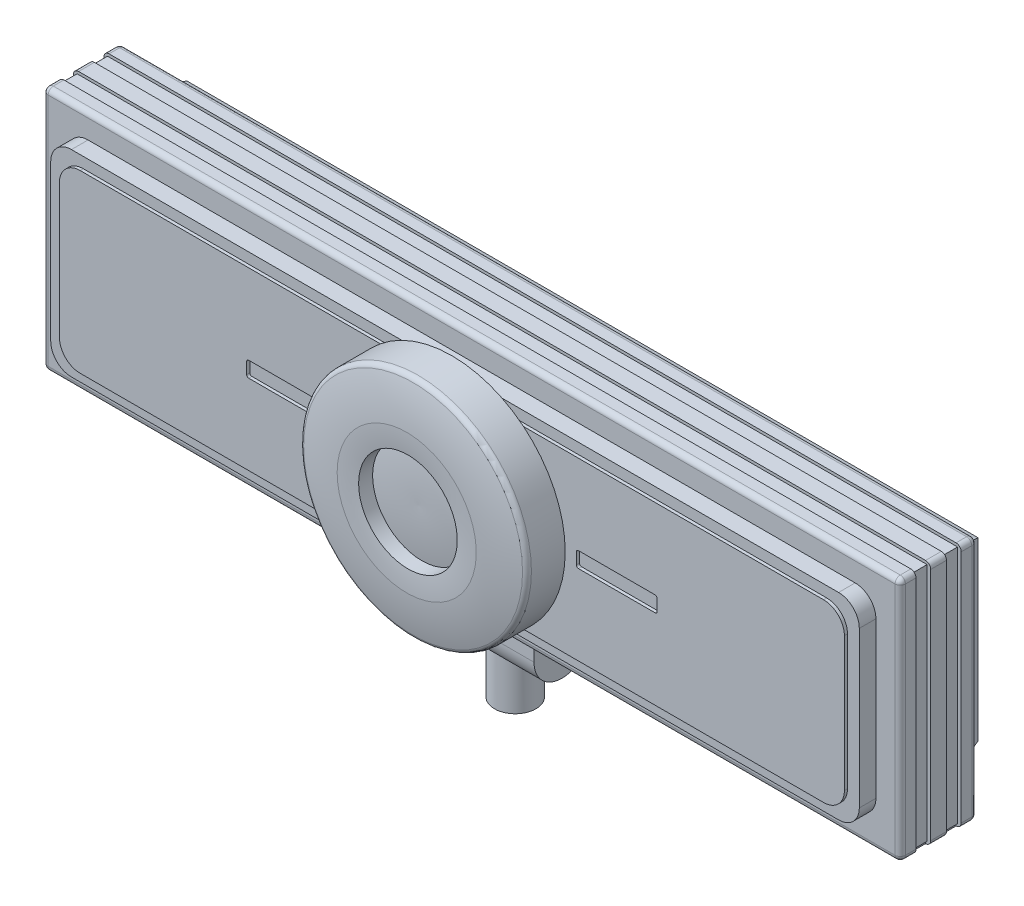
SolidWorks part; units mm, degrees
ref_plane "Front Plane" through (0, 0, 0) normal (0, 0, 1) x (1, 0, 0)
ref_plane "Top Plane" through (0, 0, 0) normal (0, 1, 0) x (1, 0, 0)
ref_plane "Right Plane" through (0, 0, 0) normal (1, 0, 0) x (0, 0, -1)
sketch "Sketch1" plane through (0, 0, 0) normal (0, 0, 1) x (1, 0, 0)
  line L1 (-52.5145, -15.0241) -> (52.5145, -15.0241)
  line L2 (-52.5145, -15.0241) -> (-52.5145, 15.0241)
  line L3 (-52.5145, 15.0241) -> (52.5145, 15.0241)
  line L4 (52.5145, -15.0241) -> (52.5145, 15.0241)
  line L5 (-52.5145, -15.0241) -> (52.5145, 15.0241) construction
  line L6 (-52.5145, 15.0241) -> (52.5145, -15.0241) construction
  point P0 (0, 0)
  dimension "D1" = 105.029
  dimension "D2" = 30.0482
extrude "Boss-Extrude1" add sketch "Sketch1" along normal blind 1.9304
sketch "Sketch2" plane through (0, 0, 1.9304) normal (0, 0, 1) x (1, 0, 0)
  line L1 (-52.07, -14.6812) -> (52.07, -14.6812)
  line L2 (-52.07, -14.6812) -> (-52.07, 14.6812)
  line L3 (-52.07, 14.6812) -> (52.07, 14.6812)
  line L4 (52.07, -14.6812) -> (52.07, 14.6812)
  line L5 (-52.07, -14.6812) -> (52.07, 14.6812) construction
  line L6 (-52.07, 14.6812) -> (52.07, -14.6812) construction
  point P0 (0, 0)
  dimension "D1" = 104.14
  dimension "D2" = 29.3624
extrude "Boss-Extrude2" add sketch "Sketch2" along normal blind 1.9304
sketch "Sketch3" plane through (0, 0, 0) normal (0, 1, 0) x (1, 0, 0)
  line L0 (0, 30.039) -> (0, -36.4807) construction
pattern_linear "LPattern1" count 2 spacing 3.7338 along (0, 0, 1) of "Boss-Extrude1", "Boss-Extrude2"
pattern_linear "LPattern2" count 2 spacing 7.4676 along (0, 0, 1) of "Boss-Extrude1"
sketch "Sketch4" plane through (0, 0, 0) normal (0, 0, -1) x (-1, 0, 0)
  line L1 (-49.4538, -11.938) -> (49.4538, -11.938)
  line L2 (-49.4538, -11.938) -> (-49.4538, 11.938)
  line L3 (-49.4538, 11.938) -> (49.4538, 11.938)
  line L4 (49.4538, -11.938) -> (49.4538, 11.938)
  line L5 (-49.4538, -11.938) -> (49.4538, 11.938) construction
  line L6 (-49.4538, 11.938) -> (49.4538, -11.938) construction
  point P0 (0, 0)
  dimension "D1" = 23.876
  dimension "D2" = 98.9076
ref_plane "Plane1" through (0, 0, -4.191) normal (0, 0, -1) x (-1, 0, 0)
sketch "Sketch5" plane through (0, 0, -4.191) normal (0, 0, -1) x (-1, 0, 0)
  line L1 (-48.4505, -10.795) -> (48.4505, -10.795)
  line L2 (-48.4505, -10.795) -> (-48.4505, 10.795)
  line L3 (-48.4505, 10.795) -> (48.4505, 10.795)
  line L4 (48.4505, -10.795) -> (48.4505, 10.795)
  line L5 (-48.4505, -10.795) -> (48.4505, 10.795) construction
  line L6 (-48.4505, 10.795) -> (48.4505, -10.795) construction
  point P0 (0, 0)
  dimension "D1" = 21.59
  dimension "D2" = 96.901
loft "Loft1" add profiles "Sketch4", "Sketch5"
fillet "Fillet1" radius 0.635 20 edges at (52.5145, 15.0241, 8.4328) (52.5145, 15.0241, 0.9652) (52.5145, 15.0241, 4.699) (52.5145, -15.0241, 8.4328) (52.5145, -15.0241, 4.699) (52.5145, -15.0241, 0.9652) (-52.5145, -15.0241, 8.4328) (-52.5145, -15.0241, 4.699) (-52.5145, -15.0241, 0.9652) (-52.5145, 15.0241, 8.4328) (-52.5145, 15.0241, 0.9652) (-52.5145, 15.0241, 4.699) (-52.5145, 0, 0) (0, -15.0241, 0) (52.5145, 0, 0) (0, 15.0241, 0) (-52.5145, 0, 9.398) (0, -15.0241, 9.398) (52.5145, 0, 9.398) (0, 15.0241, 9.398)
sketch "Sketch7" plane through (0, -14.6812, 0) normal (0, -1, 0) x (1, 0, 0)
  line L1 (-51.8795, 7.4676) -> (51.8795, 7.4676)
  line L2 (-51.8795, 7.4676) -> (-51.8795, 1.9304)
  line L3 (-51.8795, 1.9304) -> (51.8795, 1.9304)
  line L4 (51.8795, 7.4676) -> (51.8795, 1.9304)
extrude "Boss-Extrude3" add sketch "Sketch7" along normal up to surface (0.3429 mm away) up to face at (0, -15.0241, 8.1153)
sketch "Sketch8" plane through (0, 0, 9.398) normal (0, 0, 1) x (1, 0, 0)
  line L1 (-46.99, -12.065) -> (46.99, -12.065)
  line L2 (-49.53, -9.525) -> (-49.53, 9.525)
  line L3 (-46.99, 12.065) -> (46.99, 12.065)
  line L4 (49.53, -9.525) -> (49.53, 9.525)
  line L5 (-49.53, -12.065) -> (49.53, 12.065) construction
  line L6 (-49.53, 12.065) -> (49.53, -12.065) construction
  arc A0 (-49.53, 9.525) -> (-46.99, 12.065) centre (-46.99, 9.525) cw
  arc A1 (-49.53, -9.525) -> (-46.99, -12.065) centre (-46.99, -9.525) ccw
  arc A2 (46.99, -12.065) -> (49.53, -9.525) centre (46.99, -9.525) ccw
  arc A3 (49.53, 9.525) -> (46.99, 12.065) centre (46.99, 9.525) ccw
  point P0 (0, 0)
  dimension "D3" = 2.54
  dimension "D1" = 24.13
  dimension "D2" = 99.06
extrude "Boss-Extrude4" add sketch "Sketch8" along normal blind 2.032
sketch "Sketch9" plane through (0, 0, 11.43) normal (0, 0, 1) x (1, 0, 0)
  line L1 (-45.5422, -10.7569) -> (45.5422, -10.7569)
  line L2 (-48.0822, -8.2169) -> (-48.0822, 8.2169)
  line L3 (-45.5422, 10.7569) -> (45.5422, 10.7569)
  line L4 (48.0822, -8.2169) -> (48.0822, 8.2169)
  line L5 (-48.0822, -10.7569) -> (48.0822, 10.7569) construction
  line L6 (-48.0822, 10.7569) -> (48.0822, -10.7569) construction
  arc A0 (45.5422, 10.7569) -> (48.0822, 8.2169) centre (45.5422, 8.2169) cw
  arc A1 (48.0822, -8.2169) -> (45.5422, -10.7569) centre (45.5422, -8.2169) cw
  arc A2 (-48.0822, -8.2169) -> (-45.5422, -10.7569) centre (-45.5422, -8.2169) ccw
  arc A3 (-48.0822, 8.2169) -> (-45.5422, 10.7569) centre (-45.5422, 8.2169) cw
  point P0 (0, 0)
  dimension "D3" = 2.54
  dimension "D1" = 21.5138
  dimension "D2" = 96.1644
extrude "Boss-Extrude5" add sketch "Sketch9" along normal blind 0.381
sketch "Sketch11" plane through (0, 0, 0) normal (0, 1, 0) x (1, 0, 0)
  line L0 (0, -11.811) -> (0, -15.875)
  line L1 (-45.5422, -11.811) -> (45.5422, -11.811) construction
  line L2 (0, 30.039) -> (0, -36.4807) construction
  line L3 (0, -11.811) -> (13.8811, -11.811)
  line L4 (13.8811, -11.811) -> (13.8811, -16.4338)
  line L5 (0, -11.811) -> (0, -24.9316) construction
  line L6 (8.5217, -11.43) -> (8.5217, -17.3482)
  line L7 (-45.5422, -11.43) -> (45.5422, -11.43) construction
  line L8 (6.0452, -11.811) -> (6.0452, -17.1958)
  spline S0 degree 2 poles (8.5217, -17.3482) (11.2515, -17.184) (13.8811, -16.4338) knots 0 0 0 1 1 1
  spline S1 degree 2 poles (8.5217, -17.3482) (7.2787, -17.3449) (6.0452, -17.1958) knots 0 0 0 1 1 1
  spline S2 degree 2 poles (0, -15.875) (3.0436, -15.9753) (6.0452, -15.4815) knots 0 0 0 1 1 1
  dimension "D1" = 13.8811
  dimension "D2" = 4.064
  dimension "D3" = 4.6228
  dimension "D4" = 8.5217
  dimension "D5" = 5.9182
  dimension "D6" = 5.3848
  dimension "D7" = 6.0452
revolve "Revolve2" add sketch "Sketch11" angle 360 about L5
sketch "Sketch14" plane through (0, 0, 0) normal (0, 1, 0) x (1, 0, 0)
  line L0 (-8.7735, -11.811) -> (8.7735, -11.811) construction
  line L1 (0, -14.1732) -> (0, -11.811)
  line L2 (0, -11.811) -> (2.3622, -11.811)
  arc A0 (0, -14.1732) -> (2.3622, -11.811) centre (0, -11.811) ccw
  dimension "D1" = 4.7244
revolve "Revolve3" add sketch "Sketch14" angle 360 about L0
fillet "Fillet2" radius 0.635 1 edges at (-13.8811, 0, 16.4338)
sketch "Sketch15" plane through (0, 0, 11.811) normal (0, 0, 1) x (1, 0, 0)
  line L0 (-48.0822, 0) -> (48.0822, 0) construction
  line L1 (-48.0822, 8.2169) -> (-48.0822, -8.2169) construction
  line L2 (48.0822, -8.2169) -> (48.0822, 8.2169) construction
  line L3 (0, 13.4084) -> (0, -13.4084) construction
  line L4 (-15.24, 0.9525) -> (-25.146, -0.9525) construction
  line L5 (15.494, -0.9525) -> (24.892, -0.9525)
  line L6 (15.24, -0.6985) -> (15.24, 0.6985)
  line L7 (15.494, 0.9525) -> (24.892, 0.9525)
  line L8 (25.146, -0.6985) -> (25.146, 0.6985)
  line L9 (15.24, -0.9525) -> (25.146, 0.9525) construction
  line L10 (15.24, 0.9525) -> (25.146, -0.9525) construction
  line L11 (-15.24, -0.9525) -> (-25.146, 0.9525) construction
  line L12 (-25.146, -0.6985) -> (-25.146, 0.6985)
  line L13 (-15.494, 0.9525) -> (-24.892, 0.9525)
  line L14 (-15.24, -0.6985) -> (-15.24, 0.6985)
  line L15 (-15.494, -0.9525) -> (-24.892, -0.9525)
  circle A0 centre (0, 0) radius 13.4084 construction
  arc A1 (15.24, 0.6985) -> (15.494, 0.9525) centre (15.494, 0.6985) cw
  arc A2 (15.494, -0.9525) -> (15.24, -0.6985) centre (15.494, -0.6985) cw
  arc A3 (25.146, -0.6985) -> (24.892, -0.9525) centre (24.892, -0.6985) cw
  arc A4 (25.146, 0.6985) -> (24.892, 0.9525) centre (24.892, 0.6985) ccw
  arc A5 (-25.146, 0.6985) -> (-24.892, 0.9525) centre (-24.892, 0.6985) cw
  arc A6 (-25.146, -0.6985) -> (-24.892, -0.9525) centre (-24.892, -0.6985) ccw
  arc A7 (-15.494, -0.9525) -> (-15.24, -0.6985) centre (-15.494, -0.6985) ccw
  arc A8 (-15.24, 0.6985) -> (-15.494, 0.9525) centre (-15.494, 0.6985) ccw
  point P11 (20.193, 0)
  point P45 (-20.193, 0)
  dimension "D3" = 0.254
  dimension "D1" = 1.905
  dimension "D2" = 9.906
  dimension "D4" = 15.24
extrude "Cut-Extrude1" cut sketch "Sketch15" against normal blind 0.381
sketch "Sketch16" plane through (0, 0, 0) normal (1, 0, 0) x (0, 0, -1)
  line L0 (-0.635, -15.0241) -> (-7.4676, -15.0241)
  line L1 (-7.4676, -15.0241) -> (-7.4676, -17.9578)
  line L2 (-0.635, -15.0241) -> (-0.635, -17.9578)
  line L3 (-4.0513, -15.0241) -> (-4.0513, -21.3741) construction
  arc A0 (-7.4676, -17.9578) -> (-0.635, -17.9578) centre (-4.0513, -17.9578) ccw
  dimension "D1" = 6.35
extrude "Boss-Extrude6" add sketch "Sketch16" against normal mid plane 11.43
sketch "Sketch18" plane through (0, -15.0241, 0) normal (0, -1, 0) x (-1, 0, 0)
  line L0 (0, -8.4848) -> (0, -1.7932) construction
  line L1 (0, 30.039) -> (0, -36.4807) construction
  line L2 (4.3625, -4.0513) -> (0, -4.0513) construction
  line L4 (5.715, -4.0513) -> (-5.715, -4.0513) construction
  circle A0 centre (0, -4.0513) radius 2.54
  dimension "D1" = 5.08
extrude "Boss-Extrude7" add sketch "Sketch18" along normal blind 11.176
sketch "Sketch20" plane through (0, 0, 0) normal (1, 0, 0) x (0, 0, -1)
  line L0 (4.191, 0) -> (11.684, 0)
  line L1 (4.191, 10.795) -> (4.191, -10.795) construction
  line L2 (4.191, 6.604) -> (8.2804, 3.175)
  line L3 (8.2804, 3.175) -> (11.684, 3.175)
  line L4 (11.684, 3.175) -> (11.684, 0)
  line L5 (4.191, 6.604) -> (4.191, 0)
  dimension "D1" = 3.175
  dimension "D2" = 3.4036
  dimension "D3" = 7.493
  dimension "D4" = 6.604
revolve "Revolve4" add sketch "Sketch20" angle 360
